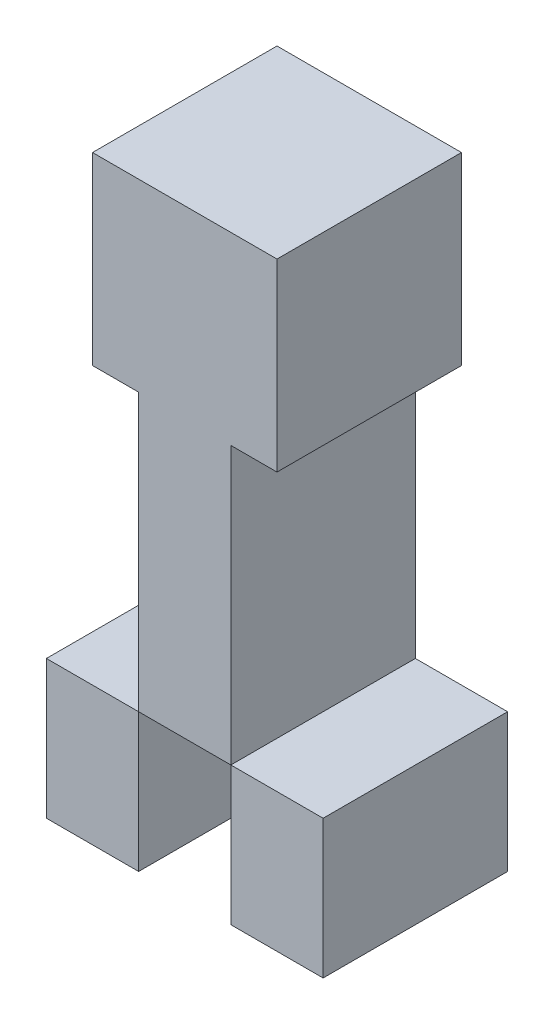
SolidWorks part; units mm, degrees
ref_plane "Front Plane" through (0, 0, 0) normal (0, 0, 1) x (1, 0, 0)
ref_plane "Top Plane" through (0, 0, 0) normal (0, 1, 0) x (1, 0, 0)
ref_plane "Right Plane" through (0, 0, 0) normal (1, 0, 0) x (0, 0, -1)
sketch "Sketch1" plane through (0, 0, 0) normal (0, 1, 0) x (1, 0, 0)
  line L1 (-114, 0) -> (-38, 0)
  line L2 (-114, 0) -> (-114, 152)
  line L3 (-114, 152) -> (-38, 152)
  line L4 (-38, 0) -> (-38, 152)
  line L5 (-111, 3) -> (-41, 3)
  line L6 (-111, 3) -> (-111, 149)
  line L7 (-111, 149) -> (-41, 149)
  line L8 (-41, 3) -> (-41, 149)
  dimension "D1" = 3
  dimension "D2" = 3
  dimension "D3" = 3
  dimension "D4" = 3
  dimension "D5" = 152
  dimension "D6" = 76
  dimension "D7" = 38
extrude "Boss-Extrude1" add sketch "Sketch1" along normal blind 114
sketch "Sketch4" plane through (0, 0, -149) normal (0, 0, 1) x (1, 0, 0)
  line L1 (-111, 114) -> (-41, 114)
  line L2 (-111, 114) -> (-111, 111)
  line L3 (-111, 111) -> (-41, 111)
  line L4 (-41, 114) -> (-41, 111)
  line L5 (-111, 114) -> (-111, 0) construction
  line L6 (-41, 114) -> (-41, 0) construction
  line L7 (-41, 114) -> (-111, 114) construction
  dimension "D1" = 3
extrude "Boss-Extrude2" add sketch "Sketch4" along normal up to surface (146 mm away) up to face at (-76, 57, -3)
mirror "Mirror2" about plane through (0, 0, 0) normal (1, 0, 0) of bodies 102
sketch "Sketch5" plane through (0, 114, 0) normal (0, 1, 0) x (1, 0, 0)
  line L0 (38, 0) -> (38, 152) construction
  line L1 (-38, 152) -> (38, 152)
  line L2 (-38, 152) -> (-38, 0)
  line L3 (-38, 0) -> (38, 0)
  line L4 (38, 152) -> (38, 0)
  line L5 (-38, 0) -> (-38, 152) construction
  line L6 (-114, 0) -> (-38, 0) construction
  line L7 (-38, 152) -> (-114, 152) construction
  line L9 (-35, 149) -> (35, 149)
  line L10 (-35, 149) -> (-35, 3)
  line L11 (-35, 3) -> (35, 3)
  line L12 (35, 149) -> (35, 3)
  dimension "D1" = 3
  dimension "D2" = 3
  dimension "D3" = 3
  dimension "D4" = 3
extrude "Boss-Extrude3" add sketch "Sketch5" along normal blind 228 separate body
sketch "Sketch6" plane through (0, 0, -152) normal (0, 0, -1) x (-1, 0, 0)
  line L0 (-38, 342) -> (38, 342) construction
  line L1 (76, 494) -> (-76, 494)
  line L2 (76, 494) -> (76, 342)
  line L3 (76, 342) -> (-76, 342)
  line L4 (-76, 494) -> (-76, 342)
  line L5 (-38, 342) -> (-38, 114) construction
  dimension "D1" = 152
  dimension "D2" = 152
  dimension "D3" = 38
extrude "Boss-Extrude4" add sketch "Sketch6" against normal up to surface (152 mm away) up to face at (0, 228, 0)
equation "\"Pikseli\"= 19mm'Yhden pikselin koko IRL"
equation "\"Seinän_paksuus\"= 3mm'Seinälevyn paksuus"
equation "\"D1@Sketch1\"=\"Seinän_paksuus\""
equation "\"D2@Sketch1\"=\"Seinän_paksuus\""
equation "\"D3@Sketch1\"=\"Seinän_paksuus\""
equation "\"D4@Sketch1\"=\"Seinän_paksuus\""
equation "\"D5@Sketch1\"=\"Pikseli\"*8"
equation "\"D6@Sketch1\"=\"Pikseli\"*4"
equation "\"D1@Sketch4\"=\"Seinän_paksuus\""
equation "\"D7@Sketch1\"=\"Pikseli\"*2"
equation "\"D1@Sketch5\"=\"Seinän_paksuus\""
equation "\"D2@Sketch5\"=\"Seinän_paksuus\""
equation "\"D3@Sketch5\"=\"Seinän_paksuus\""
equation "\"D4@Sketch5\"=\"Seinän_paksuus\""
equation "\"D1@Boss-Extrude3\"=\"Pikseli\"*12"
equation "\"D1@Sketch6\"=\"Pikseli\"*8"
equation "\"D2@Sketch6\"=\"Pikseli\"*8"
equation "\"D3@Sketch6\"=\"Pikseli\"*2"
equation "\"D1@Boss-Extrude1\"=6*\"Pikseli\""
